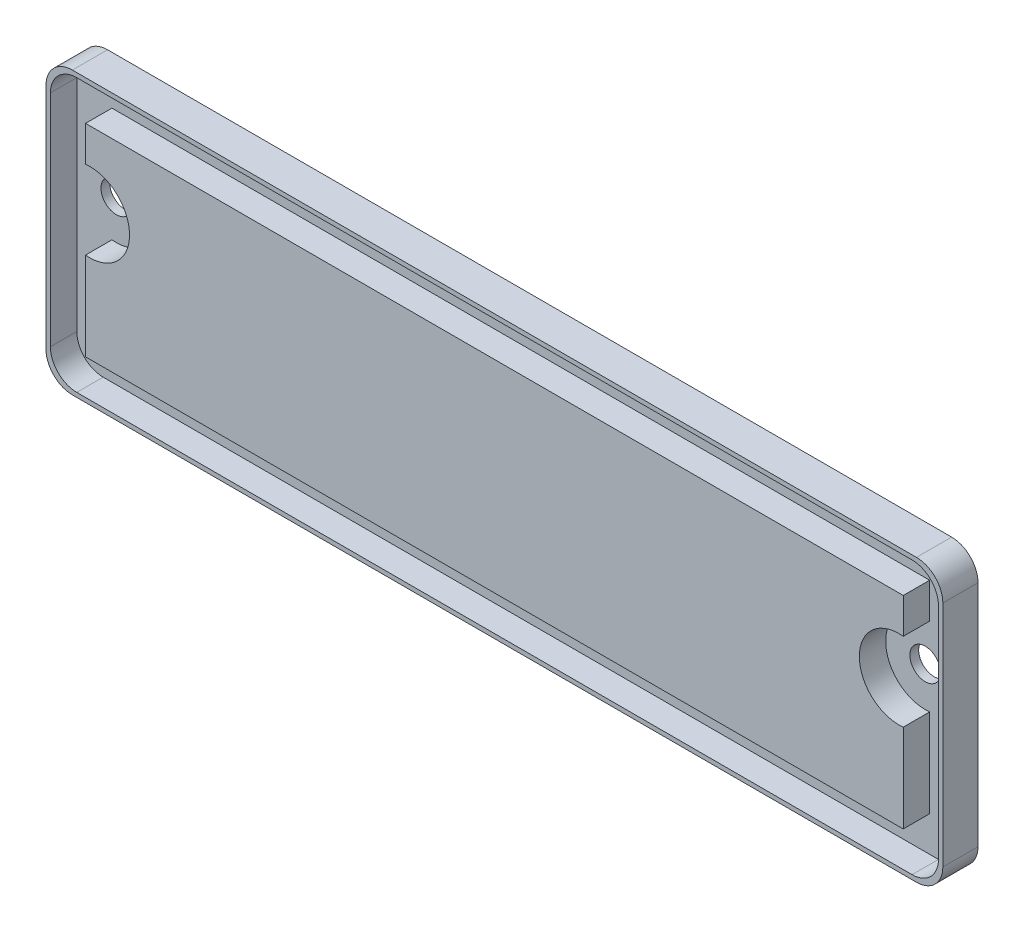
SolidWorks part; units mm, degrees
ref_plane "Front" through (0, 0, 0) normal (0, 0, 1) x (1, 0, 0)
ref_plane "Top" through (0, 0, 0) normal (0, 1, 0) x (1, 0, 0)
ref_plane "Right" through (0, 0, 0) normal (1, 0, 0) x (0, 0, -1)
sketch "Sketch1" plane through (0, 0, 0) normal (0, 0, 1) x (1, 0, 0)
  line L1 (0, 0) -> (-102, 0)
  line L2 (0, 0) -> (0, 32)
  line L3 (0, 32) -> (-102, 32)
  line L4 (-102, 0) -> (-102, 32)
  dimension "D1" = 32
  dimension "D2" = 102
extrude "Boss-Extrude1" add sketch "Sketch1" along normal blind 1
sketch "Sketch2" plane through (0, 0, 1) normal (0, 0, 1) x (1, 0, 0)
  line L0 (-102, 16) -> (0, 16) construction
  line L1 (-102, 32) -> (-102, 0) construction
  line L2 (0, 0) -> (0, 32) construction
  line L3 (0, 16) -> (-51, 32) construction
  line L4 (0, 32) -> (-102, 32) construction
  line L5 (-51, 32) -> (-51, 0) construction
  line L6 (-102, 0) -> (0, 0) construction
  line L7 (-51, 4.5) -> (-51, 27.5) construction
  line L8 (-97.5, 4.5) -> (-4.5, 4.5)
  line L9 (-97.5, 4.5) -> (-97.5, 27.5) construction
  line L10 (-97.5, 27.5) -> (-4.5, 27.5)
  line L11 (-4.5, 4.5) -> (-4.5, 27.5) construction
  line L12 (-51, 27.5) -> (-4.5, 16) construction
  line L13 (-4.5, 16) -> (-97.5, 16) construction
  line L14 (-4.5, 23.4721) -> (-4.5, 27.5)
  line L15 (-102, 32) -> (0, 32)
  line L16 (-102, 32) -> (-102, 0)
  line L17 (-102, 0) -> (0, 0)
  line L18 (0, 32) -> (0, 0)
  line L19 (-4.5, 14.5279) -> (-4.5, 4.5)
  line L20 (-97.5, 27.5) -> (-97.5, 23.4721)
  line L21 (-97.5, 23.4721) -> (-98.5113, 24.5218)
  line L22 (-97.5, 14.5279) -> (-97.5, 4.5)
  line L23 (-101.5, 31.5) -> (-0.5, 31.5)
  line L24 (-101.5, 31.5) -> (-101.5, 0.5)
  line L25 (-101.5, 0.5) -> (-0.5, 0.5)
  line L26 (-0.5, 31.5) -> (-0.5, 0.5)
  line L27 (-97.5, 4.5) -> (-98.4397, 5.5531)
  circle A0 centre (-97, 19) radius 2.25 construction
  circle A1 centre (-5, 19) radius 2.25 construction
  arc A2 (-97.5, 23.4721) -> (-97.5, 14.5279) centre (-97, 19) cw
  arc A3 (-4.5, 23.4721) -> (-4.5, 14.5279) centre (-5, 19) ccw
  dimension "D7" = 4.5
  dimension "D8" = 4.5
  dimension "D13" = 4.5
  dimension "D14" = 4.5
  dimension "D1" = 23
  dimension "D2" = 93
  dimension "D3" = 3
  dimension "D4" = 46
  dimension "D5" = 46
  dimension "D6" = 3
  dimension "D9" = 0.5
  dimension "D10" = 0.5
  dimension "D11" = 0.5
  dimension "D12" = 0.5
extrude "Boss-Extrude2" add sketch "Sketch2" along normal blind 3
sketch "Sketch3" plane through (0, 0, 1) normal (0, 0, 1) x (1, 0, 0)
  line L0 (-83.1296, 19) -> (-115.6197, 19) construction
  line L1 (-115.6197, 19) -> (4.7145, 19) construction
  line L4 (-51, 32) -> (-51, 0) construction
  line L5 (0, 32) -> (-102, 32) construction
  line L6 (-102, 0) -> (0, 0) construction
  circle A0 centre (-97, 19) radius 1.75
  circle A1 centre (-5, 19) radius 1.75
  point P16 (-12.1509, 23.3376)
  point P17 (-9.9784, 19)
  dimension "D4" = 46
  dimension "D1" = 3.5
  dimension "D2" = 3.5
  dimension "D3" = 92
extrude "Cut-Extrude1" cut sketch "Sketch3" against normal through all
fillet "Fillet1" radius 3 8 edges at (-0.5, 31.5, 2.5) (-0.5, 0.5, 2.5) (-101.5, 0.5, 2.5) (-101.5, 31.5, 2.5) (0, 0, 2) (0, 32, 2) (-102, 32, 2) (-102, 0, 2)
equation "\"LidMountingHole\"=4.5"
equation "\"D7@Sketch2\"=\"LidMountingHole\""
equation "\"D8@Sketch2\"=\"LidMountingHole\""
equation "\"WallThickness\"= 0.5"
equation "\"D12@Sketch2\"=\"WallThickness\""
equation "\"D11@Sketch2\"=\"WallThickness\""
equation "\"D10@Sketch2\"=\"WallThickness\""
equation "\"D9@Sketch2\"=\"WallThickness\""
equation "\"MountingHoleOffsetX\"=46"
equation "\"D4@Sketch2\"=\"MountingHoleOffsetX\""
equation "\"D5@Sketch2\"=\"MountingHoleOffsetX\""
equation "\"MountingHoleOffsetY\"=3"
equation "\"D6@Sketch2\"=\"MountingHoleOffsetY\""
equation "\"D3@Sketch2\"=\"MountingHoleOffsetY\""
equation "\"Hole\"=3.5"
equation "\"D1@Sketch3\"=\"Hole\""
equation "\"D2@Sketch3\"=\"Hole\""
equation "\"D13@Sketch2\"=\"LidMountingHole\""
equation "\"D14@Sketch2\"=\"LidMountingHole\""
equation "\"ScrewCutOffset\"=46"
equation "\"D3@Sketch3\"=\"ScrewCutOffset\""
equation "\"D4@Sketch3\"=\"ScrewCutOffset\""
